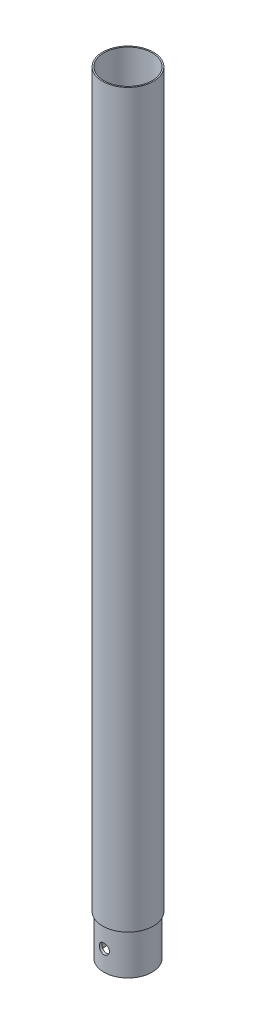
SolidWorks part; units mm, degrees
ref_plane "Front Plane" through (0, 0, 0) normal (0, 0, 1) x (1, 0, 0)
ref_plane "Top Plane" through (0, 0, 0) normal (0, 1, 0) x (1, 0, 0)
ref_plane "Right Plane" through (0, 0, 0) normal (1, 0, 0) x (0, 0, -1)
sketch "Sketch1" plane through (0, 0, 0) normal (0, 1, 0) x (1, 0, 0)
  circle A0 centre (0, 0) radius 31.75
  circle A1 centre (0, 0) radius 30.1625
  dimension "D1" = 63.5
  dimension "D2" = 1.5875
extrude "Boss-Extrude1" add sketch "Sketch1" along normal blind 914.4
sketch "Sketch3" plane through (0, 0, 0) normal (0, -1, 0) x (1, 0, 0)
  circle A0 centre (0, 0) radius 30.1625
  circle A1 centre (0, 0) radius 26.9875
  circle A2 centre (0, 0) radius 30.1625 construction
  dimension "D1" = 3.175
extrude "Boss-Extrude2" add sketch "Sketch3" against normal blind 25.4 and the other way blind 50.8
sketch "Sketch7" plane through (0, 0, 0) normal (0, 0, 1) x (1, 0, 0)
  circle A0 centre (0, -25.4) radius 6.35
  dimension "D1" = 12.7
  dimension "D2" = 25.4
extrude "Cut-Extrude2" cut sketch "Sketch7" against normal through all and the other way through all
